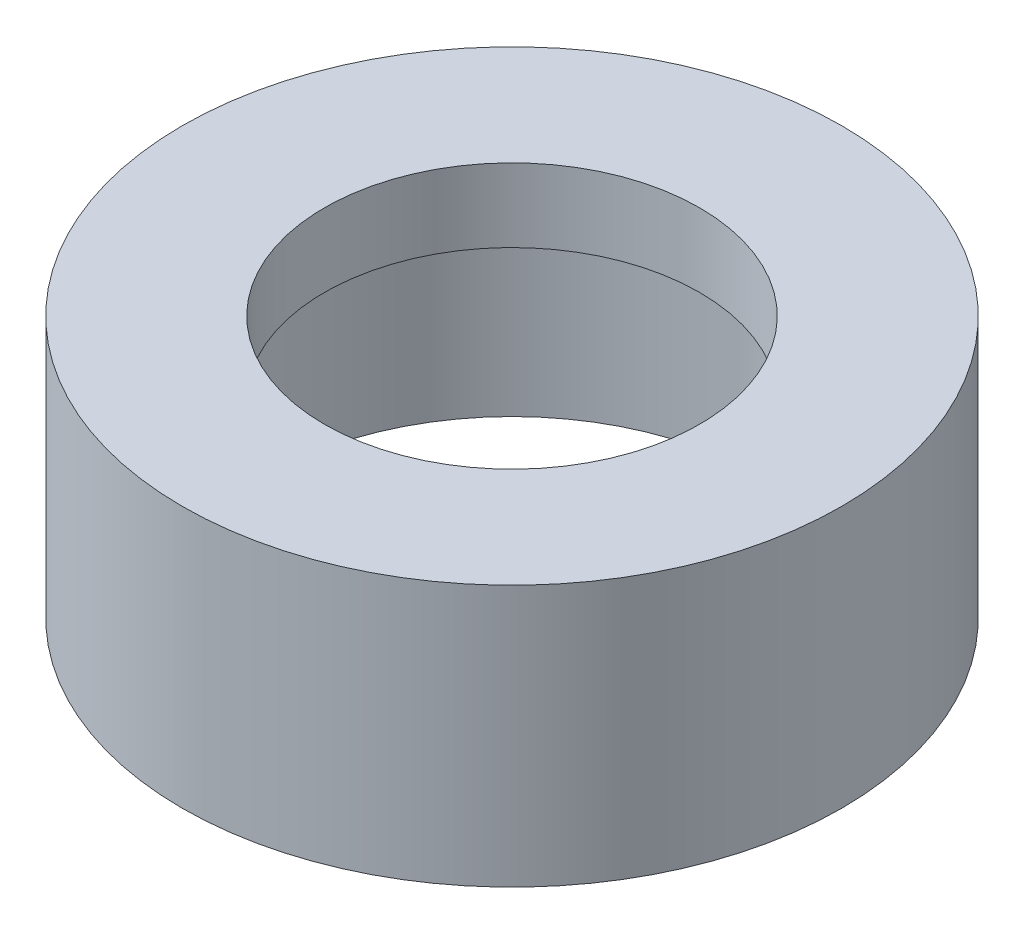
SolidWorks part; units mm, degrees
ref_plane "Front Plane" through (0, 0, 0) normal (0, 0, 1) x (1, 0, 0)
ref_plane "Top Plane" through (0, 0, 0) normal (0, 1, 0) x (1, 0, 0)
ref_plane "Right Plane" through (0, 0, 0) normal (1, 0, 0) x (0, 0, -1)
sketch "Sketch2" plane through (0, 0, 0) normal (0, 1, 0) x (1, 0, 0)
  circle A0 centre (0, 0) radius 29
extrude "Extrude1" add sketch "Sketch2" along normal blind 23
sketch "Sketch3" plane through (0, 0, 0) normal (0, -1, 0) x (1, 0, 0)
  circle A0 centre (0, 0) radius 21.7
extrude "Cut-Extrude1" cut sketch "Sketch3" against normal blind 16.55
sketch "Sketch4" plane through (0, 23, 0) normal (0, 1, 0) x (1, 0, 0)
  circle A0 centre (0, 0) radius 16.5
extrude "Cut-Extrude2" cut sketch "Sketch4" against normal through all
sketch "Sketch5" plane through (0, 23, 0) normal (0, 1, 0) x (1, 0, 0)
  circle A0 centre (0, 25.2305) radius 1.5
  circle A1 centre (21.8502, 12.6152) radius 1.5
  circle A2 centre (21.8502, -12.6152) radius 1.5
  circle A3 centre (0, -25.2305) radius 1.5
  circle A4 centre (-21.8502, -12.6152) radius 1.5
  circle A5 centre (-21.8502, 12.6152) radius 1.5
extrude "Cut-Extrude3" cut sketch "Sketch5" against normal through all from offset 3
